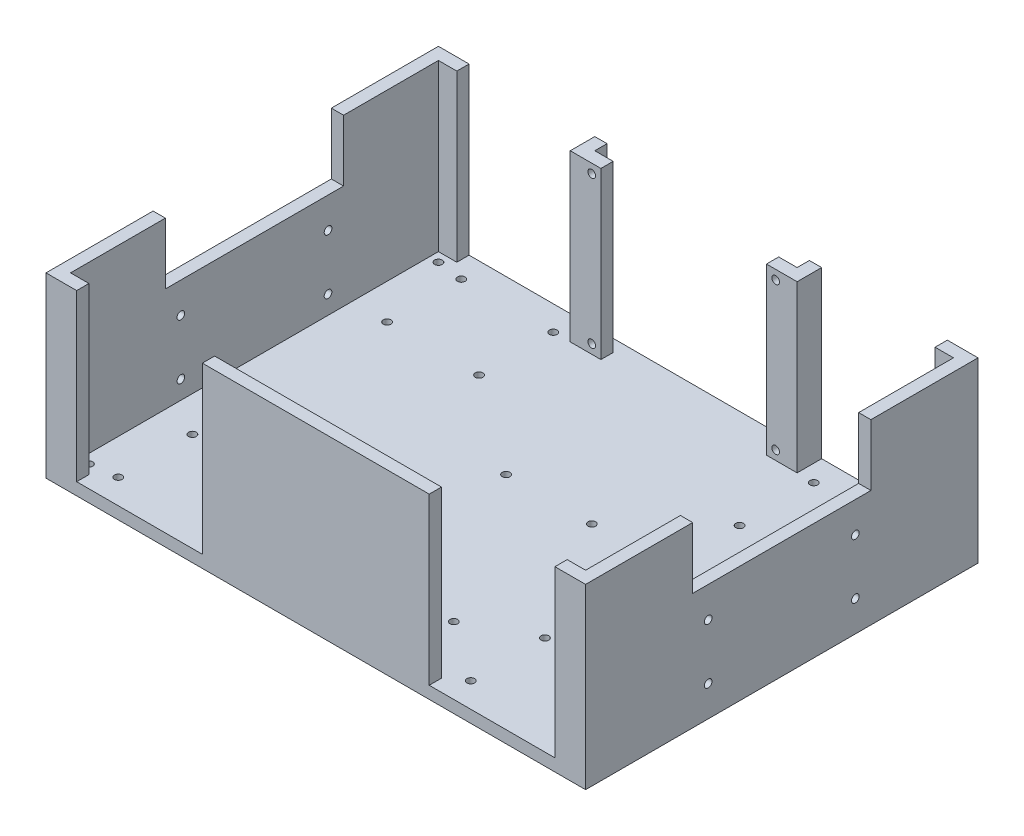
SolidWorks part; units mm, degrees
ref_plane "前视基准面" through (0, 0, 0) normal (0, 0, 1) x (1, 0, 0)
ref_plane "上视基准面" through (0, 0, 0) normal (0, 1, 0) x (1, 0, 0)
ref_plane "右视基准面" through (0, 0, 0) normal (1, 0, 0) x (0, 0, -1)
sketch "草图1" plane through (0, 0, 0) normal (0, 1, 0) x (1, 0, 0)
  line L1 (0, 0) -> (176, 0)
  line L2 (0, 0) -> (0, -128)
  line L3 (0, -128) -> (176, -128)
  line L4 (176, 0) -> (176, -128)
  point P4 (0, 0)
  dimension "D1" = 128
  dimension "D2" = 176
extrude "凸台-拉伸1" add sketch "草图1" along normal blind 58
sketch "草图2" plane through (0, 58, 0) normal (0, 1, 0) x (1, 0, 0)
  line L0 (172, -4) -> (4, -4)
  line L1 (4, -4) -> (4, -124)
  line L2 (4, -124) -> (172, -124)
  line L3 (172, -124) -> (172, -4)
extrude "切除-拉伸1" cut sketch "草图2" against normal blind 54
sketch "草图3" plane through (0, 0, 128) normal (0, 0, 1) x (1, 0, 0)
  line L0 (10, 58) -> (10, 4)
  line L1 (0, 58) -> (176, 58) construction
  line L3 (10, 4) -> (51, 4)
  line L4 (51, 4) -> (51, 58)
  line L5 (51, 58) -> (10, 58)
  line L6 (0, 58) -> (0, 0) construction
  line L7 (176, 58) -> (176, 0) construction
  line L8 (125, 58) -> (166, 58)
  line L9 (125, 58) -> (125, 4)
  line L10 (125, 4) -> (166, 4)
  line L11 (166, 58) -> (166, 4)
  line L12 (0, 0) -> (176, 0) construction
  dimension "D1" = 41
  dimension "D2" = 10
  dimension "D3" = 10
  dimension "D4" = 41
  dimension "D5" = 4
  dimension "D6" = 4
extrude "切除-拉伸2" cut sketch "草图3" against normal through all
sketch "草图5" plane through (0, 0, 0) normal (-1, 0, 0) x (0, 0, 1)
  line L0 (64, 58) -> (64, 0) construction
  line L1 (0, 58) -> (128, 58) construction
  line L2 (0, 0) -> (128, 0) construction
  line L4 (34.9327, 58) -> (93.0673, 58)
  line L5 (34.9327, 58) -> (34.9327, 37.9893)
  line L6 (34.9327, 37.9893) -> (93.0673, 37.9893)
  line L7 (93.0673, 58) -> (93.0673, 37.9893)
extrude "切除-拉伸4" cut sketch "草图5" against normal through all contours L5 L6 L7 L4
sketch "草图6" plane through (0, 0, 0) normal (-1, 0, 0) x (0, 0, 1)
  line L0 (64, 37.9893) -> (64, 0) construction
  line L1 (34.9327, 37.9893) -> (93.0673, 37.9893) construction
  line L2 (0, 0) -> (128, 0) construction
  point P6 (40, 27.9893)
  point P7 (88, 27.9893)
  point P8 (40, 10)
  point P9 (88, 10)
  point P10 (0, 0)
  point P11 (0, 0)
  dimension "D1" = 24
  dimension "D2" = 24
  dimension "D3" = 10
  dimension "D4" = 10
hole_wizard "M3 螺纹孔1" positions "草图7" profile "草图8" tap size "M3" standard "GB" end condition through all
sketch "草图7" plane through (0, 0, 0) normal (-1, 0, 0) x (0, 0, 1)
  point P0 (40, 27.9893)
  point P3 (88, 27.9893)
  point P6 (88, 10)
  point P9 (40, 10)
sketch "草图8" plane through (0, 27.9893, 40) normal (0, 1, 0) x (0, 0, 1)
  line L0 (0, 0) -> (0, 176)
  line L1 (0, 176) -> (1.25, 176)
  line L2 (1.25, 176) -> (1.25, 0)
  line L5 (1.25, 0) -> (0, 0)
  line L11 (0, -6.35) -> (0, 107.95) construction
  dimension "通孔螺纹孔钻头直径" = 2.5
  dimension "通孔螺纹孔钻头深度" = 176
cosmetic thread "孔螺蚊线1" parameters "D2"=3
cosmetic thread "孔螺蚊线2" parameters "D2"=3
cosmetic thread "孔螺蚊线3" parameters "D2"=3
cosmetic thread "孔螺蚊线4" parameters "D2"=3
sketch "草图9" plane through (0, 4, 0) normal (0, 1, 0) x (1, 0, 0)
  line L0 (0, -64) -> (176, -64) construction
  line L1 (0, -34.9327) -> (0, -93.0673) construction
  line L2 (176, -34.9327) -> (176, -93.0673) construction
  line L3 (88, 0) -> (88, -128) construction
  line L4 (125, 0) -> (51, 0) construction
  line L5 (51, -128) -> (125, -128) construction
  line L6 (0, 0) -> (0, -34.9327) construction
  line L11 (10, 0) -> (0, 0) construction
  line L13 (10, -128) -> (51, -128) construction
  line L14 (0, -93.0673) -> (0, -128) construction
  point P12 (7, -7)
  point P13 (7, -121)
  point P14 (169, -121)
  point P15 (169, -7)
  point P20 (15.5, -95.75)
  point P21 (15.5, -119.95)
  point P22 (45.5, -119.95)
  point P23 (45.5, -95.75)
  point P24 (130.5, -95.75)
  point P25 (130.5, -119.95)
  point P26 (160.5, -119.95)
  point P27 (160.5, -95.75)
  point P28 (130.5, -8.05)
  point P29 (130.5, -32.25)
  point P30 (160.5, -32.25)
  point P31 (160.5, -8.05)
  point P32 (15.5, -8.05)
  point P33 (15.5, -32.25)
  point P34 (45.5, -32.25)
  point P35 (45.5, -8.05)
  point P36 (0, 0)
  point P37 (0, 0)
  point P38 (0, 0)
  point P39 (0, 0)
  point P46 (0, 0)
  point P47 (2.1384, -94.6025)
  point P52 (21.6182, -98.1674)
  dimension "D1" = 7
  dimension "D2" = 7
  dimension "D3" = 8.05
  dimension "D4" = 8.05
  dimension "D5" = 30
  dimension "D6" = 15.5
  dimension "D7" = 24.2
  dimension "D8" = 24.2
  dimension "D9" = 30
  dimension "D10" = 15.5
sketch "草图11" plane through (0, 4, 0) normal (0, 1, 0) x (1, 0, 0)
  line L0 (51, -128) -> (125, -128) construction
  point P0 (62.77, -106)
  point P1 (111.03, -106)
  point P2 (105.95, -55.92)
  point P3 (78.01, -55.92)
  dimension "D1" = 22
  dimension "D2" = 22
  dimension "D3" = 48.26
  dimension "D4" = 50.08
  dimension "D5" = 50.08
  dimension "D6" = 15.24
  dimension "D7" = 5.08
  dimension "D8" = 17.27
hole_wizard "M3 螺纹孔2" positions "草图12" profile "草图13" tap size "M3" standard "GB" end condition through all
sketch "草图12" plane through (0, 4, 0) normal (0, 1, 0) x (1, 0, 0)
  point P0 (7, -7)
  point P3 (15.5, -8.05)
  point P6 (15.5, -32.25)
  point P9 (45.5, -32.25)
  point P12 (45.5, -8.05)
  point P15 (15.5, -95.75)
  point P18 (15.5, -119.95)
  point P21 (7, -121)
  point P24 (45.5, -119.95)
  point P27 (45.5, -95.75)
  point P30 (130.5, -119.95)
  point P33 (160.5, -119.95)
  point P36 (160.5, -95.75)
  point P39 (130.5, -95.75)
  point P42 (169, -121)
  point P45 (169, -7)
  point P48 (160.5, -8.05)
  point P51 (160.5, -32.25)
  point P54 (130.5, -32.25)
  point P57 (130.5, -8.05)
  point P60 (105.95, -55.92)
  point P63 (111.03, -106)
  point P66 (62.77, -106)
  point P69 (78.01, -55.92)
sketch "草图13" plane through (7, 4, 7) normal (1, 0, 0) x (0, 0, 1)
  line L0 (0, 0) -> (0, 4)
  line L1 (0, 4) -> (1.25, 4)
  line L2 (1.25, 4) -> (1.25, 0)
  line L5 (1.25, 0) -> (0, 0)
  line L11 (0, -6.35) -> (0, 107.95) construction
  dimension "通孔螺纹孔钻头直径" = 2.5
  dimension "通孔螺纹孔钻头深度" = 4
cosmetic thread "孔螺蚊线5" parameters "D2"=3
cosmetic thread "孔螺蚊线6" parameters "D2"=3
cosmetic thread "孔螺蚊线7" parameters "D2"=3
cosmetic thread "孔螺蚊线8" parameters "D2"=3
cosmetic thread "孔螺蚊线9" parameters "D2"=3
cosmetic thread "孔螺蚊线10" parameters "D2"=3
cosmetic thread "孔螺蚊线11" parameters "D2"=3
cosmetic thread "孔螺蚊线12" parameters "D2"=3
cosmetic thread "孔螺蚊线13" parameters "D2"=3
cosmetic thread "孔螺蚊线14" parameters "D2"=3
cosmetic thread "孔螺蚊线15" parameters "D2"=3
cosmetic thread "孔螺蚊线16" parameters "D2"=3
cosmetic thread "孔螺蚊线17" parameters "D2"=3
cosmetic thread "孔螺蚊线18" parameters "D2"=3
cosmetic thread "孔螺蚊线19" parameters "D2"=3
cosmetic thread "孔螺蚊线20" parameters "D2"=3
cosmetic thread "孔螺蚊线21" parameters "D2"=3
cosmetic thread "孔螺蚊线22" parameters "D2"=3
cosmetic thread "孔螺蚊线23" parameters "D2"=3
cosmetic thread "孔螺蚊线24" parameters "D2"=3
cosmetic thread "孔螺蚊线25" parameters "D2"=3
cosmetic thread "孔螺蚊线26" parameters "D2"=3
cosmetic thread "孔螺蚊线27" parameters "D2"=3
cosmetic thread "孔螺蚊线28" parameters "D2"=3
sketch "草图15" plane through (0, 4, 0) normal (0, 1, 0) x (1, 0, 0)
  line L1 (51, 0) -> (125, 0)
  line L2 (51, 0) -> (51, -8)
  line L3 (51, -8) -> (125, -8)
  line L4 (125, 0) -> (125, -8)
  line L5 (125, 0) -> (125, -4) construction
  dimension "D1" = 8
extrude "凸台-拉伸2" add sketch "草图15" along normal blind 54
sketch "草图16" plane through (0, 58, 0) normal (0, 1, 0) x (1, 0, 0)
  line L0 (55, 0) -> (55, -4)
  line L1 (125, 0) -> (51, 0) construction
  line L2 (55, -4) -> (61, -4)
  line L3 (61, -4) -> (61, -8)
  line L4 (51, -8) -> (125, -8) construction
  line L5 (61, -8) -> (115, -8)
  line L6 (51, -8) -> (125, -8) construction
  line L7 (115, -8) -> (115, -4)
  line L8 (115, -4) -> (121, -4)
  line L9 (121, -4) -> (121, 0)
  line L10 (55, 0) -> (121, 0)
  line L11 (51, 0) -> (51, -8) construction
  line L12 (125, 0) -> (125, -8) construction
  dimension "D1" = 4
  dimension "D2" = 4
  dimension "D3" = 4
  dimension "D4" = 4
  dimension "D5" = 6
  dimension "D6" = 6
extrude "切除-拉伸5" cut sketch "草图16" against normal blind 54
sketch "草图19" plane through (0, 0, 4) normal (0, 0, -1) x (-1, 0, 0)
  line L0 (-88, 58) -> (-88, 4) construction
  line L1 (-51, 58) -> (-125, 58) construction
  line L2 (0, 4) -> (-176, 4) construction
  line L3 (-125, 31) -> (-51, 31) construction
  line L4 (-125, 58) -> (-125, 4) construction
  line L5 (-51, 4) -> (-51, 58) construction
  line L6 (-121, 4) -> (-121, 58) construction
  point P6 (-118, 7)
  point P7 (-58, 7)
  point P8 (-58, 55)
  point P9 (-118, 55)
  dimension "D1" = 3
  dimension "D2" = 3
hole_wizard "M3 螺纹孔4" positions "草图23" profile "草图24" tap size "M3" standard "GB"
sketch "草图23" plane through (0, 0, 4) normal (0, 0, -1) x (-1, 0, 0)
  point P0 (-118, 55)
  point P3 (-58, 55)
  point P6 (-58, 7)
  point P9 (-118, 7)
sketch "草图24" plane through (118, 55, 4) normal (1, 0, 0) x (0, 1, 0)
  line L0 (0, 0) -> (0, 4)
  line L1 (0, 4) -> (1.25, 4)
  line L2 (1.25, 4) -> (1.25, 0)
  line L5 (1.25, 0) -> (0, 0)
  line L11 (0, -6.35) -> (0, 107.95) construction
  dimension "通孔螺纹孔钻头直径" = 2.5
  dimension "通孔螺纹孔钻头深度" = 4
cosmetic thread "孔螺蚊线33" parameters "D2"=3
cosmetic thread "孔螺蚊线34" parameters "D2"=3
cosmetic thread "孔螺蚊线35" parameters "D2"=3
cosmetic thread "孔螺蚊线36" parameters "D2"=3
